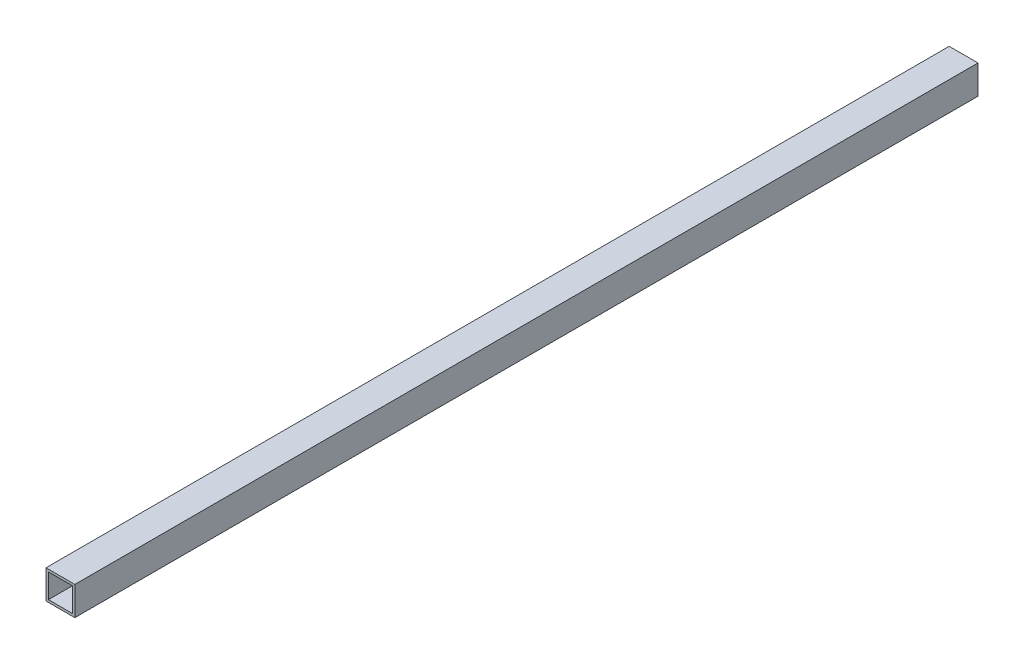
SolidWorks part; units mm, degrees
material "6061 Alloy"
ref_plane "Front Plane" through (0, 0, 0) normal (0, 0, 1) x (1, 0, 0)
ref_plane "Top Plane" through (0, 0, 0) normal (0, 1, 0) x (1, 0, 0)
ref_plane "Right Plane" through (0, 0, 0) normal (1, 0, 0) x (0, 0, -1)
sketch "Sketch1" plane through (0, 0, 0) normal (0, 0, 1) x (1, 0, 0)
  line L0 (19.05, 0) -> (15.875, 0) construction
  line L1 (-19.05, 0) -> (19.05, 0) construction
  line L2 (0, 19.05) -> (0, -19.05)
  point P7 (0, 0)
sketch "Sketch2" plane through (0, 0, 0) normal (1, 0, 0) x (0, 0, -1)
  line L0 (596.9, 0) -> (-596.9, 0)
  point P4 (0, 0)
  dimension "Length" = 1193.8
sketch "Sketch3" plane through (0, 0, 0) normal (0, 0, 1) x (1, 0, 0)
  line L0 (-19.05, 0) -> (19.05, 0) construction
  line L5 (19.05, -19.05) -> (-19.05, -19.05)
  line L6 (19.05, -19.05) -> (19.05, 19.05)
  line L11 (19.05, 19.05) -> (-19.05, 19.05)
  line L12 (-19.05, -19.05) -> (-19.05, 19.05)
  line L14 (19.05, -19.05) -> (-19.05, 19.05) construction
  line L15 (19.05, 19.05) -> (-19.05, -19.05) construction
  line L16 (15.875, -15.875) -> (-15.875, -15.875)
  line L17 (15.875, -15.875) -> (15.875, 15.875)
  line L18 (15.875, 15.875) -> (-15.875, 15.875)
  line L19 (-15.875, -15.875) -> (-15.875, 15.875)
  line L20 (15.875, -15.875) -> (-15.875, 15.875) construction
  line L21 (15.875, 15.875) -> (-15.875, -15.875) construction
  point P0 (0, 0)
  point P5 (0, 0)
  point P13 (15.875, -19.05)
  dimension "D1" = 3.175
  dimension "D3" = 38.1
  dimension "D4" = 38.1
  dimension "D2" = 3.175
extrude "Boss-Extrude1" add sketch "Sketch3" along normal up to vertex (596.9 mm away) and the other way up to vertex (596.9 mm away) up to point (0, 0, 596.9) other way up to point (0, 0, -596.9)
sketch "Sketch5" plane through (0, 0, 0) normal (1, 0, 0) x (0, 0, -1)
  line L0 (-596.9, 0) -> (596.9, 0) construction
  line L3 (-596.9, -19.05) -> (-596.9, 19.05) construction
  line L4 (596.9, -19.05) -> (596.9, 19.05) construction
  point P6 (-554.0375, 0)
  point P7 (-539.75, 0)
  point P8 (539.75, 0)
  point P10 (554.0375, 0)
  dimension "D1" = 42.8625
  dimension "D2" = 57.15
  dimension "D3" = 42.8625
  dimension "D4" = 57.15
equation "\"D1@Sketch3\"=\"Wall thickness@Sketch1\""
equation "\"D1@Sketch5\"=\"Width@Sketch1\"*1.125"
equation "\"D2@Sketch5\"=\"Width@Sketch1\"*1.5"
equation "\"D3@Sketch5\"=\"D1@Sketch5\""
equation "\"D4@Sketch5\"=\"D2@Sketch5\""
equation "\"D2@Sketch3\"=\"Wall Thickness@Sketch1\""
